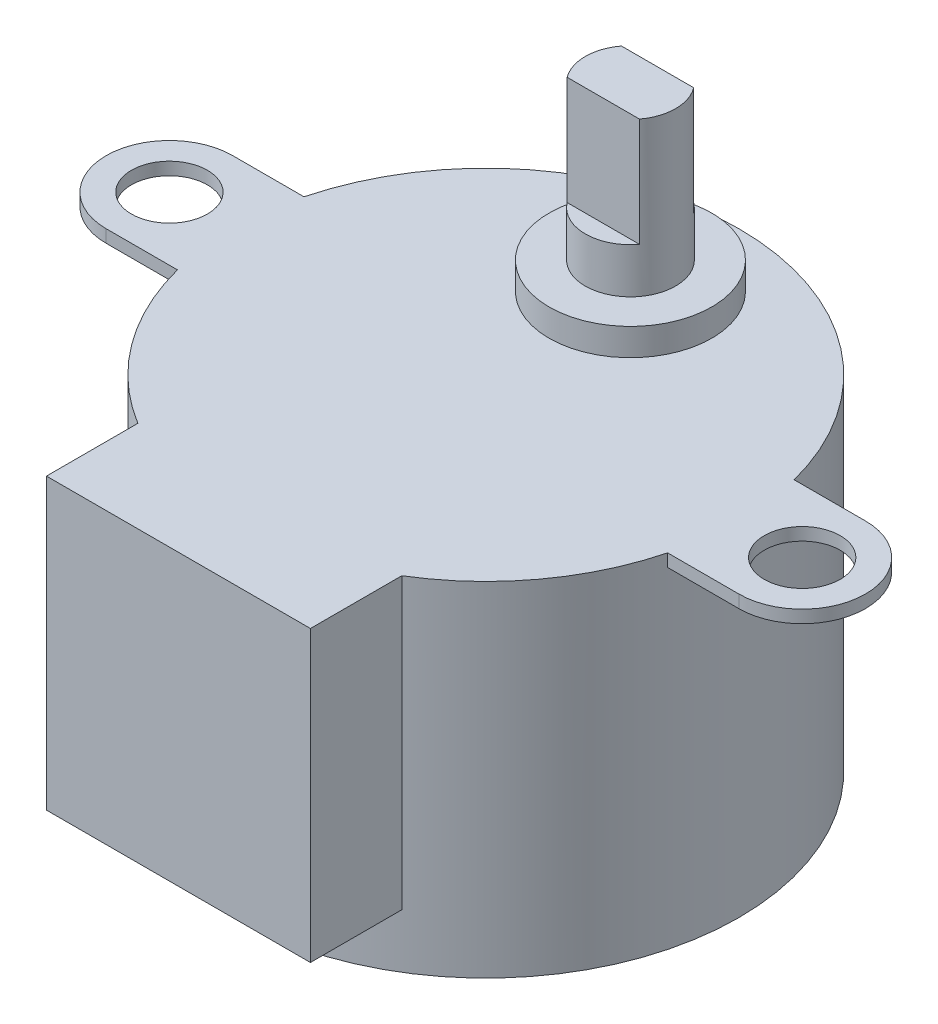
SolidWorks part; units mm, degrees
ref_plane "Front Plane" through (0, 0, 0) normal (0, 0, 1) x (1, 0, 0)
ref_plane "Top Plane" through (0, 0, 0) normal (0, 1, 0) x (1, 0, 0)
ref_plane "Right Plane" through (0, 0, 0) normal (1, 0, 0) x (0, 0, -1)
sketch "Sketch1" plane through (0, 0, 0) normal (0, 1, 0) x (1, 0, 0)
  circle A0 centre (0, 0) radius 14
extrude "Boss-Extrude2" add sketch "Sketch1" along normal blind 19
sketch "Sketch2" plane through (0, 19, 0) normal (0, 1, 0) x (1, 0, 0)
  line L0 (-24.7817, 0) -> (24.1965, 0) construction
  line L1 (-17.5377, 3.5) -> (17.5, 3.5)
  line L2 (-17.5, -3.5) -> (17.5, -3.5)
  line L3 (0, 16.5144) -> (0, -16.7702) construction
  circle A0 centre (17.5, 0) radius 2.1
  circle A1 centre (-17.5, 0) radius 2.1
  arc A2 (17.5, -3.5) -> (17.5, 3.5) centre (17.5, 0) ccw
  arc A3 (-17.5, -3.5) -> (-17.5, 3.5) centre (-17.5, 0) cw
  circle M9 centre (0, 0) radius 14
  dimension "D2" = 17.5
  dimension "D1" = 3.5
extrude "Boss-Extrude4" add sketch "Sketch2" against normal blind 0.7 contours L2 A2 L1 A0 M9 | A3 L2 L1 A1 M9
sketch "Sketch3" plane through (0, 19, 0) normal (0, 1, 0) x (1, 0, 0)
  line L0 (-22.4641, 0) -> (22.1508, 0) construction
  line L1 (0, 15.8568) -> (0, -23.3871) construction
  line L2 (-7.3, -11.9461) -> (-7.3, -17)
  line L3 (7.3, -11.9461) -> (7.3, -17)
  line L4 (-7.3, -17) -> (7.3, -17)
  arc A0 (-13.5554, -3.5) -> (13.5554, -3.5) centre (0, 0) ccw construction
  arc A3 (-13.5554, -3.5) -> (13.5554, -3.5) centre (0, 0) ccw
  arc A4 (-7.3, -11.9461) -> (7.3, -11.9461) centre (0, 0) ccw
  dimension "D1" = 7.3
  dimension "D2" = 17
  dimension "D3" = 0
extrude "Boss-Extrude5" add sketch "Sketch3" against normal blind 16
sketch "Sketch4" plane through (0, 19, 0) normal (0, 1, 0) x (1, 0, 0)
  line L0 (22.0255, 0) -> (-22.3701, 0) construction
  line L1 (0, 15.2306) -> (0, -19.2019) construction
  circle A0 centre (0, 8) radius 4.5
  dimension "D1" = 8
extrude "Boss-Extrude6" add sketch "Sketch4" along normal blind 1.5
sketch "Sketch5" plane through (0, 20.5, 0) normal (0, 1, 0) x (1, 0, 0)
  circle A0 centre (0, 8) radius 2.5
extrude "Boss-Extrude7" add sketch "Sketch5" along normal blind 8.5
sketch "Sketch7" plane through (0, 29, 0) normal (0, 1, 0) x (1, 0, 0)
  line L1 (-2, 9.5) -> (2, 9.5)
  line L2 (-2, 6.5) -> (2, 6.5)
  arc A0 (2, 9.5) -> (-2, 9.5) centre (0, 8) ccw
  arc A1 (-2, 6.5) -> (2, 6.5) centre (0, 8) ccw
extrude "Cut-Extrude1" cut sketch "Sketch7" against normal blind 6
